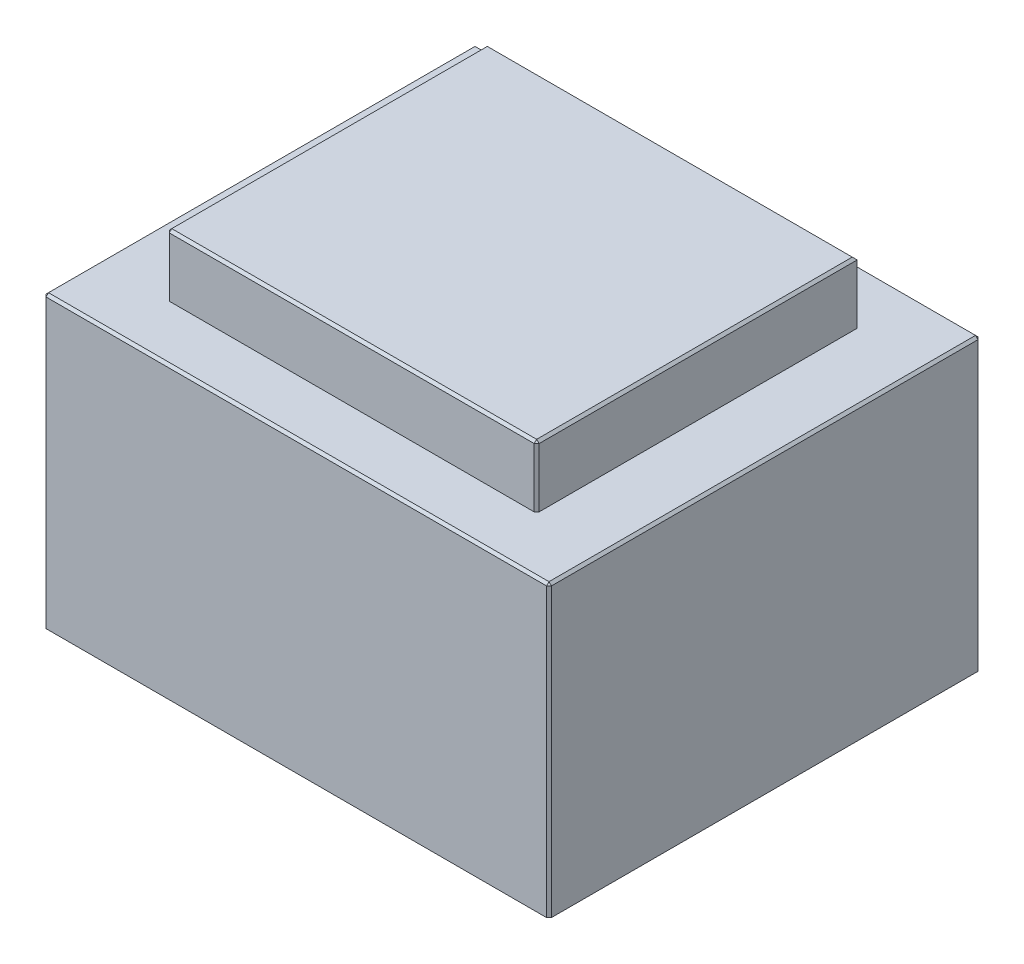
SolidWorks part; units mm, degrees
ref_plane "Front Plane" through (0, 0, 0) normal (0, 0, 1) x (1, 0, 0)
ref_plane "Top Plane" through (0, 0, 0) normal (0, 1, 0) x (1, 0, 0)
ref_plane "Right Plane" through (0, 0, 0) normal (1, 0, 0) x (0, 0, -1)
sketch "Sketch2" plane through (0, 0, 0) normal (0, 1, 0) x (1, 0, 0)
  line L0 (0, 33.0534) -> (0, -29.8287) construction
  line L1 (-43.3034, 0) -> (39.3876, 0) construction
  line L3 (20.5, -17.5) -> (-20.5, -17.5)
  line L4 (20.5, -17.5) -> (20.5, 17.5)
  line L5 (20.5, 17.5) -> (-20.5, 17.5)
  line L6 (-20.5, -17.5) -> (-20.5, 17.5)
  line L7 (20.5, -17.5) -> (-20.5, 17.5) construction
  line L8 (20.5, 17.5) -> (-20.5, -17.5) construction
  point P5 (0, 0)
  dimension "D1" = 41
  dimension "D2" = 35
extrude "Boss-Extrude1" add sketch "Sketch2" along normal blind 23.5
sketch "Sketch3" plane through (0, 23.5, 0) normal (0, 1, 0) x (1, 0, 0)
  line L1 (-15, 13) -> (15, 13)
  line L2 (-15, 13) -> (-15, -13)
  line L3 (-15, -13) -> (15, -13)
  line L4 (15, 13) -> (15, -13)
  line L5 (-15, 13) -> (15, -13) construction
  line L6 (-15, -13) -> (15, 13) construction
  point P0 (0, 0)
  dimension "D1" = 30
  dimension "D2" = 26
extrude "Boss-Extrude2" add sketch "Sketch3" along normal blind 5
sketch "Sketch4" plane through (0, 0, 0) normal (0, -1, 0) x (1, 0, 0)
  line L0 (-25.6893, 0) -> (27.0586, 0) construction
  line L1 (-25.6893, 12.5) -> (26.4013, 12.5) construction
  line L2 (-25.6893, -12.5) -> (27.7707, -12.5) construction
  line L3 (0, 18.596) -> (0, -19.5819) construction
  circle A0 centre (-10, 12.5) radius 0.4
  circle A1 centre (10, 12.5) radius 0.4
  circle A2 centre (-5, -12.5) radius 0.4
  circle A3 centre (5, -12.5) radius 0.4
  dimension "D5" = 0.8
  dimension "D1" = 12.5
  dimension "D2" = 12.5
  dimension "D3" = 20
  dimension "D4" = 10
extrude "Boss-Extrude3" add sketch "Sketch4" along normal blind 2.5
chamfer "Chamfer1" distance 0.2 angle 45 15 edges at (-15, 26, -13) (-15, 26, 13) (0, 28.5, 13) (-15, 28.5, 0) (0, 28.5, -13) (15, 28.5, 0) (15, 26, 13) (-20.5, 11.75, -17.5) (20.5, 11.75, -17.5) (20.5, 11.75, 17.5) (-20.5, 11.75, 17.5) (-20.5, 23.5, 0) (0, 23.5, -17.5) (20.5, 23.5, 0) (0, 23.5, 17.5)
